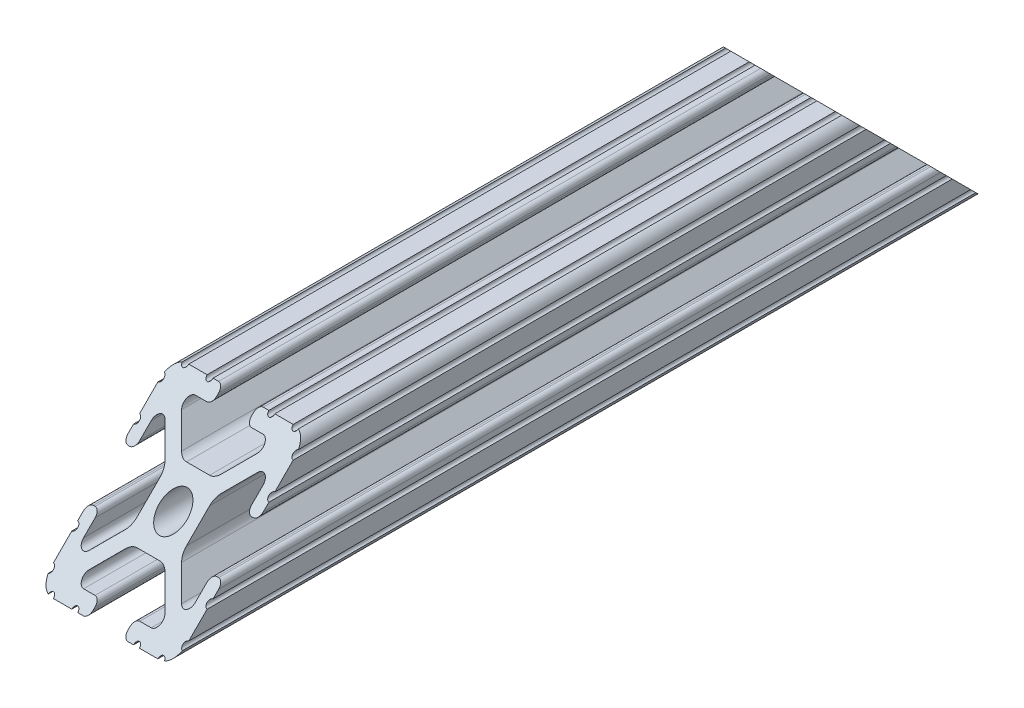
SolidWorks part; units mm, degrees
ref_plane "Front Plane" through (0, 0, 0) normal (0, 0, 1) x (1, 0, 0)
ref_plane "Top Plane" through (0, 0, 0) normal (0, 1, 0) x (1, 0, 0)
ref_plane "Right Plane" through (0, 0, 0) normal (1, 0, 0) x (0, 0, -1)
sketch "Sketch2" plane through (0, 0, 0) normal (0, 0, 1) x (1, 0, 0)
  line L0 (-3.7373, -5.2999) -> (-7.1039, -8.6665)
  line L1 (-6.3485, -10.4902) -> (-4.1904, -10.4902)
  line L2 (-3.2512, -11.4294) -> (-3.2512, -11.7608)
  line L3 (-4.1904, -12.7) -> (-5.2436, -12.7)
  line L4 (-6.3485, -12.7) -> (-9.8037, -12.7)
  line L5 (-12.7, -9.8037) -> (-12.7, -6.3485)
  line L6 (-12.7, -5.2436) -> (-12.7, -4.1904)
  line L7 (-11.7608, -3.2512) -> (-11.4294, -3.2512)
  line L8 (-10.4902, -4.1904) -> (-10.4902, -6.3485)
  line L9 (-8.6665, -7.1039) -> (-5.2999, -3.7373)
  line L10 (-4.6482, -2.164) -> (-4.6482, 2.164)
  line L11 (-8.6665, 7.1039) -> (-5.2999, 3.7373)
  line L12 (-10.4902, 4.1904) -> (-10.4902, 6.3485)
  line L13 (-11.7608, 3.2512) -> (-11.4294, 3.2512)
  line L14 (-12.7, 5.2436) -> (-12.7, 4.1904)
  line L15 (-12.7, 9.8037) -> (-12.7, 6.3485)
  line L16 (-6.3485, 12.7) -> (-9.8037, 12.7)
  line L17 (-4.1904, 12.7) -> (-5.2436, 12.7)
  line L18 (-3.2512, 11.4294) -> (-3.2512, 11.7608)
  line L19 (-6.3485, 10.4902) -> (-4.1904, 10.4902)
  line L20 (-3.7373, 5.2999) -> (-7.1039, 8.6665)
  line L21 (-2.164, 4.6482) -> (2.164, 4.6482)
  line L22 (3.7373, 5.2999) -> (7.1039, 8.6665)
  line L23 (6.3485, 10.4902) -> (4.1904, 10.4902)
  line L24 (3.2512, 11.4294) -> (3.2512, 11.7608)
  line L25 (4.1904, 12.7) -> (5.2436, 12.7)
  line L26 (6.3485, 12.7) -> (9.8037, 12.7)
  line L27 (12.7, 9.8037) -> (12.7, 6.3485)
  line L28 (12.7, 5.2436) -> (12.7, 4.1904)
  line L29 (11.7608, 3.2512) -> (11.4294, 3.2512)
  line L30 (10.4902, 4.1904) -> (10.4902, 6.3485)
  line L31 (8.6665, 7.1039) -> (5.2999, 3.7373)
  line L32 (3.2512, -11.4294) -> (3.2512, -11.7608)
  line L33 (6.3485, -10.4902) -> (4.1904, -10.4902)
  line L34 (3.7373, -5.2999) -> (7.1039, -8.6665)
  line L35 (-2.164, -4.6482) -> (2.164, -4.6482)
  line L36 (4.6482, -2.164) -> (4.6482, 2.164)
  line L37 (8.6665, -7.1039) -> (5.2999, -3.7373)
  line L38 (10.4902, -4.1904) -> (10.4902, -6.3485)
  line L39 (11.7608, -3.2512) -> (11.4294, -3.2512)
  line L40 (12.7, -5.2436) -> (12.7, -4.1904)
  line L41 (6.3485, -12.7) -> (9.8037, -12.7)
  line L42 (12.7, -9.8037) -> (12.7, -6.3485)
  line L43 (4.1904, -12.7) -> (5.2436, -12.7)
  circle A0 centre (0, 0) radius 2.6035
  arc A1 (12.7, -9.8037) -> (12.58, -10.8954) centre (12.7, -10.3562) ccw
  arc A2 (10.8954, -12.58) -> (9.8037, -12.7) centre (10.3562, -12.7) ccw
  arc A3 (6.3485, -12.7) -> (5.2436, -12.7) centre (5.796, -12.7) ccw
  arc A4 (-2.164, -4.6482) -> (-3.7373, -5.2999) centre (-2.164, -6.8732) ccw
  arc A5 (-7.1039, -8.6665) -> (-6.3485, -10.4902) centre (-6.3485, -9.4219) ccw
  arc A6 (-3.2512, -11.4294) -> (-4.1904, -10.4902) centre (-4.1904, -11.4294) ccw
  arc A7 (-4.1904, -12.7) -> (-3.2512, -11.7608) centre (-4.1904, -11.7608) ccw
  arc A8 (-5.2436, -12.7) -> (-6.3485, -12.7) centre (-5.796, -12.7) ccw
  arc A9 (-9.8037, -12.7) -> (-10.8954, -12.58) centre (-10.3562, -12.7) ccw
  arc A10 (-12.58, -10.8954) -> (-10.8954, -12.58) centre (-10.1173, -10.1173) ccw
  arc A11 (-12.58, -10.8954) -> (-12.7, -9.8037) centre (-12.7, -10.3562) ccw
  arc A12 (-12.7, -6.3485) -> (-12.7, -5.2436) centre (-12.7, -5.796) ccw
  arc A13 (-11.7608, -3.2512) -> (-12.7, -4.1904) centre (-11.7608, -4.1904) ccw
  arc A14 (-10.4902, -4.1904) -> (-11.4294, -3.2512) centre (-11.4294, -4.1904) ccw
  arc A15 (-10.4902, -6.3485) -> (-8.6665, -7.1039) centre (-9.4219, -6.3485) ccw
  arc A16 (-5.2999, -3.7373) -> (-4.6482, -2.164) centre (-6.8732, -2.164) ccw
  arc A17 (-4.6482, 2.164) -> (-5.2999, 3.7373) centre (-6.8732, 2.164) ccw
  arc A18 (-8.6665, 7.1039) -> (-10.4902, 6.3485) centre (-9.4219, 6.3485) ccw
  arc A19 (-11.4294, 3.2512) -> (-10.4902, 4.1904) centre (-11.4294, 4.1904) ccw
  arc A20 (-12.7, 4.1904) -> (-11.7608, 3.2512) centre (-11.7608, 4.1904) ccw
  arc A21 (-12.7, 5.2436) -> (-12.7, 6.3485) centre (-12.7, 5.796) ccw
  arc A22 (-12.7, 9.8037) -> (-12.58, 10.8954) centre (-12.7, 10.3562) ccw
  arc A23 (-10.8954, 12.58) -> (-12.58, 10.8954) centre (-10.1173, 10.1173) ccw
  arc A24 (-10.8954, 12.58) -> (-9.8037, 12.7) centre (-10.3562, 12.7) ccw
  arc A25 (-6.3485, 12.7) -> (-5.2436, 12.7) centre (-5.796, 12.7) ccw
  arc A26 (-3.2512, 11.7608) -> (-4.1904, 12.7) centre (-4.1904, 11.7608) ccw
  arc A27 (-4.1904, 10.4902) -> (-3.2512, 11.4294) centre (-4.1904, 11.4294) ccw
  arc A28 (-6.3485, 10.4902) -> (-7.1039, 8.6665) centre (-6.3485, 9.4219) ccw
  arc A29 (-3.7373, 5.2999) -> (-2.164, 4.6482) centre (-2.164, 6.8732) ccw
  arc A30 (2.164, 4.6482) -> (3.7373, 5.2999) centre (2.164, 6.8732) ccw
  arc A31 (7.1039, 8.6665) -> (6.3485, 10.4902) centre (6.3485, 9.4219) ccw
  arc A32 (3.2512, 11.4294) -> (4.1904, 10.4902) centre (4.1904, 11.4294) ccw
  arc A33 (4.1904, 12.7) -> (3.2512, 11.7608) centre (4.1904, 11.7608) ccw
  arc A34 (5.2436, 12.7) -> (6.3485, 12.7) centre (5.796, 12.7) ccw
  arc A35 (9.8037, 12.7) -> (10.8954, 12.58) centre (10.3562, 12.7) ccw
  arc A36 (12.58, 10.8954) -> (10.8954, 12.58) centre (10.1173, 10.1173) ccw
  arc A37 (12.58, 10.8954) -> (12.7, 9.8037) centre (12.7, 10.3562) ccw
  arc A38 (12.7, 6.3485) -> (12.7, 5.2436) centre (12.7, 5.796) ccw
  arc A39 (11.7608, 3.2512) -> (12.7, 4.1904) centre (11.7608, 4.1904) ccw
  arc A40 (10.4902, 4.1904) -> (11.4294, 3.2512) centre (11.4294, 4.1904) ccw
  arc A41 (10.4902, 6.3485) -> (8.6665, 7.1039) centre (9.4219, 6.3485) ccw
  arc A42 (5.2999, 3.7373) -> (4.6482, 2.164) centre (6.8732, 2.164) ccw
  arc A43 (12.7, -5.2436) -> (12.7, -6.3485) centre (12.7, -5.796) ccw
  arc A44 (4.1904, -10.4902) -> (3.2512, -11.4294) centre (4.1904, -11.4294) ccw
  arc A45 (6.3485, -10.4902) -> (7.1039, -8.6665) centre (6.3485, -9.4219) ccw
  arc A46 (3.7373, -5.2999) -> (2.164, -4.6482) centre (2.164, -6.8732) ccw
  arc A47 (4.6482, -2.164) -> (5.2999, -3.7373) centre (6.8732, -2.164) ccw
  arc A48 (8.6665, -7.1039) -> (10.4902, -6.3485) centre (9.4219, -6.3485) ccw
  arc A49 (11.4294, -3.2512) -> (10.4902, -4.1904) centre (11.4294, -4.1904) ccw
  arc A50 (12.7, -4.1904) -> (11.7608, -3.2512) centre (11.7608, -4.1904) ccw
  arc A51 (10.8954, -12.58) -> (12.58, -10.8954) centre (10.1173, -10.1173) ccw
  arc A52 (3.2512, -11.7608) -> (4.1904, -12.7) centre (4.1904, -11.7608) ccw
extrude "Boss-Extrude1" add sketch "Sketch2" along normal blind 152.4
sketch "Sketch3" plane through (-12.7, 0, 0) normal (-1, 0, 0) x (0, 0, 1)
  line L3 (0, 12.58) -> (0, -12.58)
  line L4 (0, -12.58) -> (43.2939, 30.7139)
  line L5 (43.2939, 30.7139) -> (0, 30.7139)
  line L6 (0, 30.7139) -> (0, 12.58)
  line L7 (152.4, -12.7) -> (90.5015, 49.1985)
  line L8 (90.5015, 49.1985) -> (152.4, 49.1985)
  line L9 (152.4, 49.1985) -> (152.4, -12.7)
  line L10 (152.4, 9.8037) -> (152.4, 6.3485) construction
  dimension "D1" = 45
  dimension "D2" = 45
extrude "Cut-Extrude2" cut sketch "Sketch3" against normal blind 203.2
